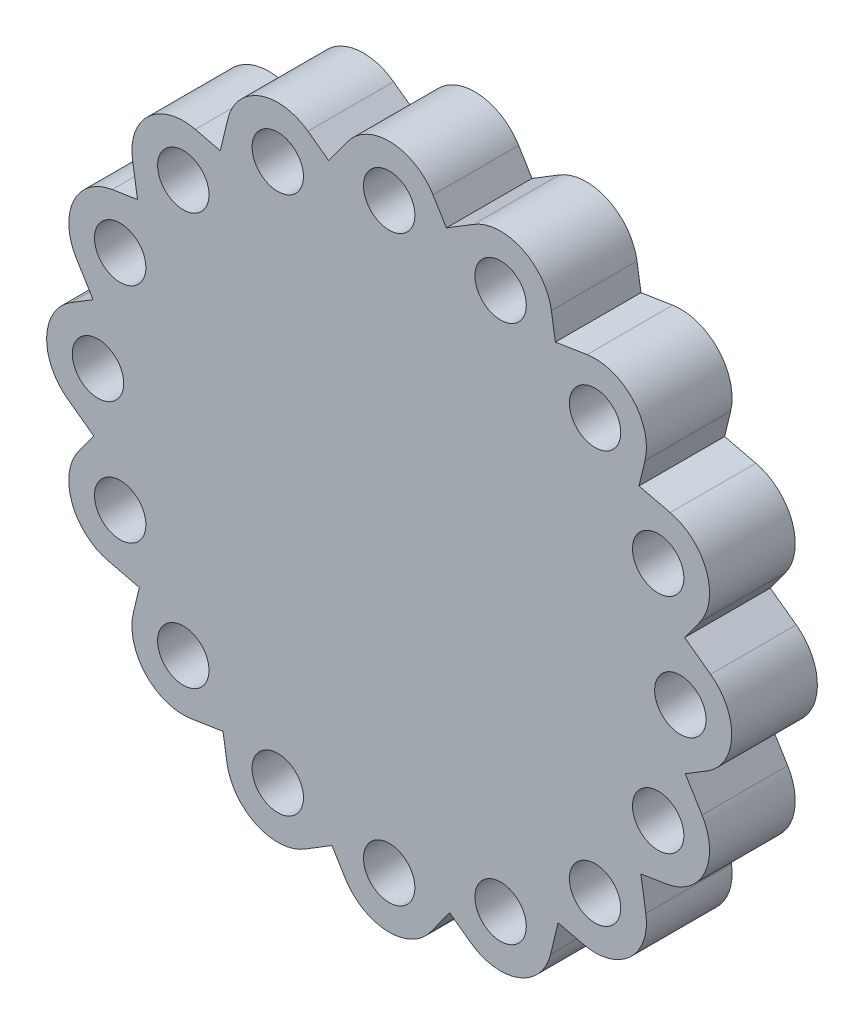
SolidWorks part; units mm, degrees
ref_plane "Top" through (0, 0, 0) normal (0, 0, 1) x (1, 0, 0)
ref_plane "Сверху" through (0, 0, 0) normal (0, 1, 0) x (1, 0, 0)
ref_plane "Справа" through (0, 0, 0) normal (1, 0, 0) x (0, 0, -1)
sketch "Sketch1" plane through (0, 0, 0) normal (0, 0, 1) x (1, 0, 0)
  line L0 (0, -21.7471) -> (0, 22.4263) construction
  line L1 (3.3418, 17.2868) -> (4.9395, 18.2647)
  line L2 (9.4689, 16.1737) -> (9.7028, 14.6921)
  line L3 (2.5587, 18.5662) -> (3.3418, 17.2868)
  line L4 (9.7028, 14.6921) -> (11.5531, 14.9841)
  line L5 (14.9376, 11.319) -> (14.5866, 9.8606)
  line L6 (14.5866, 9.8606) -> (16.4078, 9.4224)
  line L7 (18.1321, 4.741) -> (17.2498, 3.5279)
  line L8 (17.2498, 3.5279) -> (18.7646, 2.4261)
  line L9 (18.5662, -2.5587) -> (17.2868, -3.3418)
  line L10 (17.2868, -3.3418) -> (18.2647, -4.9395)
  line L11 (16.1737, -9.4689) -> (14.6921, -9.7028)
  line L12 (14.6921, -9.7028) -> (14.9841, -11.5531)
  line L13 (11.319, -14.9376) -> (9.8606, -14.5866)
  line L14 (9.8606, -14.5866) -> (9.4224, -16.4078)
  line L15 (4.741, -18.1321) -> (3.5279, -17.2498)
  line L16 (3.5279, -17.2498) -> (2.4261, -18.7646)
  line L17 (-2.5587, -18.5662) -> (-3.3418, -17.2868)
  line L18 (-3.3418, -17.2868) -> (-4.9395, -18.2647)
  line L19 (-9.4689, -16.1737) -> (-9.7028, -14.6921)
  line L20 (-9.7028, -14.6921) -> (-11.5531, -14.9841)
  line L21 (-14.9376, -11.319) -> (-14.5866, -9.8606)
  line L22 (-14.5866, -9.8606) -> (-16.4078, -9.4224)
  line L23 (-18.1321, -4.741) -> (-17.2498, -3.5279)
  line L24 (-17.2498, -3.5279) -> (-18.7646, -2.4261)
  line L25 (-18.5662, 2.5587) -> (-17.2868, 3.3418)
  line L26 (-17.2868, 3.3418) -> (-18.2647, 4.9395)
  line L27 (-16.1737, 9.4689) -> (-14.6921, 9.7028)
  line L28 (-14.6921, 9.7028) -> (-14.9841, 11.5531)
  line L29 (-11.319, 14.9376) -> (-9.8606, 14.5866)
  line L30 (-9.8606, 14.5866) -> (-9.4224, 16.4078)
  line L31 (-4.741, 18.1321) -> (-3.5279, 17.2498)
  line L32 (-3.5279, 17.2498) -> (-2.4261, 18.7646)
  circle A1 centre (0, 17) radius 1.5
  circle A2 centre (6.5056, 15.706) radius 1.5
  circle A3 centre (12.0208, 12.0208) radius 1.5
  circle A4 centre (15.706, 6.5056) radius 1.5
  circle A5 centre (17, 0) radius 1.5
  circle A6 centre (15.706, -6.5056) radius 1.5
  circle A7 centre (12.0208, -12.0208) radius 1.5
  circle A8 centre (6.5056, -15.706) radius 1.5
  circle A9 centre (0, -17) radius 1.5
  circle A10 centre (-6.5056, -15.706) radius 1.5
  circle A11 centre (-12.0208, -12.0208) radius 1.5
  circle A12 centre (-15.706, -6.5056) radius 1.5
  circle A13 centre (-17, 0) radius 1.5
  circle A14 centre (-15.706, 6.5056) radius 1.5
  circle A15 centre (-12.0208, 12.0208) radius 1.5
  circle A16 centre (-6.5056, 15.706) radius 1.5
  arc A17 (2.5587, 18.5662) -> (0, 20) centre (0, 17) ccw
  arc A18 (7.6537, 18.4776) -> (4.9395, 18.2647) centre (6.5056, 15.706) ccw
  arc A19 (9.4689, 16.1737) -> (7.6537, 18.4776) centre (6.5056, 15.706) ccw
  arc A20 (14.1421, 14.1421) -> (11.5531, 14.9841) centre (12.0208, 12.0208) ccw
  arc A21 (14.9376, 11.319) -> (14.1421, 14.1421) centre (12.0208, 12.0208) ccw
  arc A22 (18.4776, 7.6537) -> (16.4078, 9.4224) centre (15.706, 6.5056) ccw
  arc A23 (18.1321, 4.741) -> (18.4776, 7.6537) centre (15.706, 6.5056) ccw
  arc A24 (20, 0) -> (18.7646, 2.4261) centre (17, 0) ccw
  arc A25 (18.5662, -2.5587) -> (20, 0) centre (17, 0) ccw
  arc A26 (18.4776, -7.6537) -> (18.2647, -4.9395) centre (15.706, -6.5056) ccw
  arc A27 (16.1737, -9.4689) -> (18.4776, -7.6537) centre (15.706, -6.5056) ccw
  arc A28 (14.1421, -14.1421) -> (14.9841, -11.5531) centre (12.0208, -12.0208) ccw
  arc A29 (11.319, -14.9376) -> (14.1421, -14.1421) centre (12.0208, -12.0208) ccw
  arc A30 (7.6537, -18.4776) -> (9.4224, -16.4078) centre (6.5056, -15.706) ccw
  arc A31 (4.741, -18.1321) -> (7.6537, -18.4776) centre (6.5056, -15.706) ccw
  arc A32 (0, -20) -> (2.4261, -18.7646) centre (0, -17) ccw
  arc A33 (-2.5587, -18.5662) -> (0, -20) centre (0, -17) ccw
  arc A34 (-7.6537, -18.4776) -> (-4.9395, -18.2647) centre (-6.5056, -15.706) ccw
  arc A35 (-9.4689, -16.1737) -> (-7.6537, -18.4776) centre (-6.5056, -15.706) ccw
  arc A36 (-14.1421, -14.1421) -> (-11.5531, -14.9841) centre (-12.0208, -12.0208) ccw
  arc A37 (-14.9376, -11.319) -> (-14.1421, -14.1421) centre (-12.0208, -12.0208) ccw
  arc A38 (-18.4776, -7.6537) -> (-16.4078, -9.4224) centre (-15.706, -6.5056) ccw
  arc A39 (-18.1321, -4.741) -> (-18.4776, -7.6537) centre (-15.706, -6.5056) ccw
  arc A40 (-20, 0) -> (-18.7646, -2.4261) centre (-17, 0) ccw
  arc A41 (-18.5662, 2.5587) -> (-20, 0) centre (-17, 0) ccw
  arc A42 (-18.4776, 7.6537) -> (-18.2647, 4.9395) centre (-15.706, 6.5056) ccw
  arc A43 (-16.1737, 9.4689) -> (-18.4776, 7.6537) centre (-15.706, 6.5056) ccw
  arc A44 (-14.1421, 14.1421) -> (-14.9841, 11.5531) centre (-12.0208, 12.0208) ccw
  arc A45 (-11.319, 14.9376) -> (-14.1421, 14.1421) centre (-12.0208, 12.0208) ccw
  arc A46 (-7.6537, 18.4776) -> (-9.4224, 16.4078) centre (-6.5056, 15.706) ccw
  arc A47 (-4.741, 18.1321) -> (-7.6537, 18.4776) centre (-6.5056, 15.706) ccw
  arc A48 (0, 20) -> (-2.4261, 18.7646) centre (0, 17) ccw
  point P39 (0, 0)
  point P40 (0, 0)
  point P151 (0, 0)
  dimension "D1" = 16
  dimension "D2" = 16
extrude "Boss-Extrude1" add sketch "Sketch1" along normal blind 5
